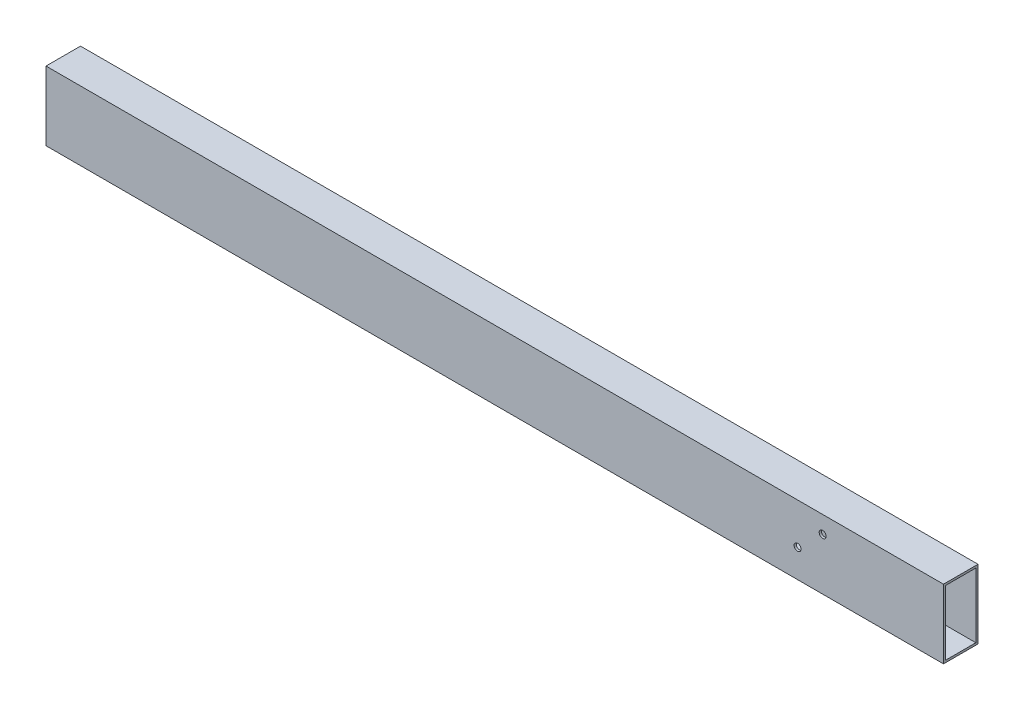
SolidWorks part; units mm, degrees
ref_plane "Front Plane" through (0, 0, 0) normal (0, 0, 1) x (1, 0, 0)
ref_plane "Top Plane" through (0, 0, 0) normal (0, 1, 0) x (1, 0, 0)
ref_plane "Right Plane" through (0, 0, 0) normal (1, 0, 0) x (0, 0, -1)
sketch "Sketch1" plane through (0, 0, 0) normal (1, 0, 0) x (0, 0, -1)
  line L0 (-9.1895, -23.8125) -> (-9.1895, 23.8125)
  line L1 (-10.777, -25.4) -> (14.623, -25.4)
  line L2 (-10.777, -25.4) -> (-10.777, 25.4)
  line L3 (-10.777, 25.4) -> (14.623, 25.4)
  line L4 (14.623, -25.4) -> (14.623, 25.4)
  line L5 (-10.777, -25.4) -> (14.623, 25.4) construction
  line L6 (-10.777, 25.4) -> (14.623, -25.4) construction
  line L11 (-9.1895, 23.8125) -> (13.0355, 23.8125)
  line L12 (13.0355, -23.8125) -> (13.0355, 23.8125)
  line L13 (-9.1895, -23.8125) -> (13.0355, -23.8125)
  dimension "D1" = 50.8
  dimension "D2" = 25.4
  dimension "D3" = 1.5875
extrude "Boss-Extrude1" add sketch "Sketch1" along normal mid plane 660.4
hole_wizard "#10 Clearance Hole1" positions "Sketch3" profile "Sketch4" hole size "#10" standard "ANSI Inch" end condition through all
sketch "Sketch3" plane through (0, 0, -14.623) normal (0, 0, -1) x (-1, 0, 0)
  line L0 (-330.2, 25.4) -> (330.2, 25.4) construction
  line L1 (-330.2, -25.4) -> (-330.2, 25.4) construction
  point P0 (-241.3, 12.7)
  point P7 (-222.8323, -4.7386)
  dimension "D1" = 12.7
  dimension "D2" = 88.9
  dimension "D3" = 25.4
sketch "Sketch4" plane through (241.3, 12.7, -14.623) normal (1, 0, 0) x (0, 1, 0)
  line L0 (0, 0) -> (0, 25.4)
  line L1 (0, 25.4) -> (2.5527, 25.4)
  line L2 (2.5527, 25.4) -> (2.5527, 0)
  line L5 (2.5527, 0) -> (0, 0)
  line L11 (0, -6.35) -> (0, 107.95) construction
  dimension "Thru Hole Dia." = 5.1054
  dimension "Thru Hole Depth" = 25.4
